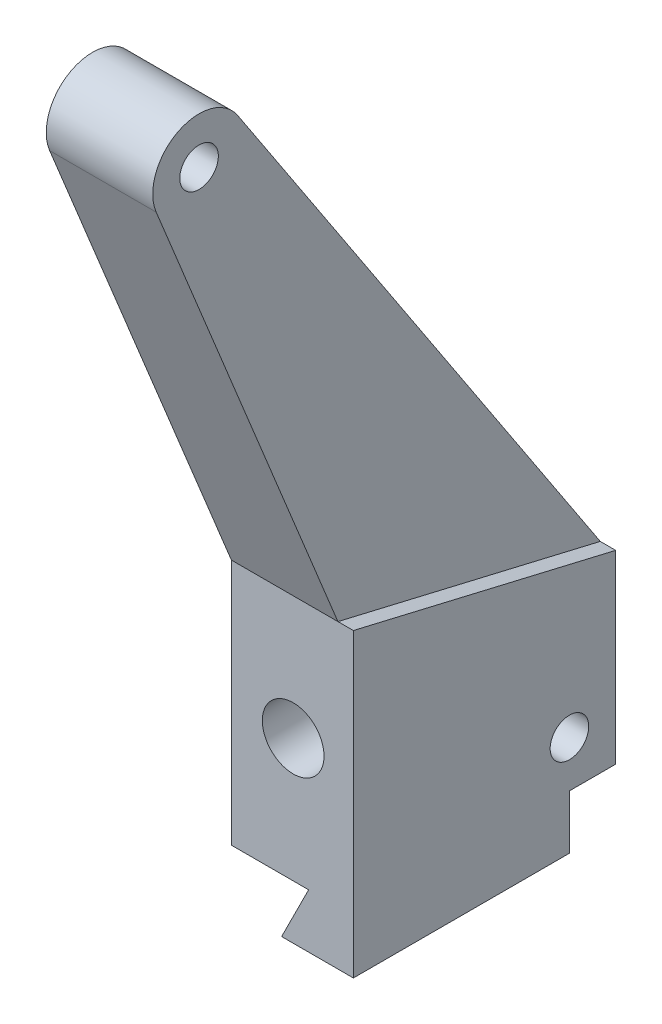
SolidWorks part; units mm, degrees
ref_plane "Front Plane" through (0, 0, 0) normal (0, 0, 1) x (1, 0, 0)
ref_plane "Top Plane" through (0, 0, 0) normal (0, 1, 0) x (1, 0, 0)
ref_plane "Right Plane" through (0, 0, 0) normal (1, 0, 0) x (0, 0, -1)
sketch "Sketch1" plane through (0, 0, 0) normal (1, 0, 0) x (0, 0, -1)
  line L0 (0, 0) -> (0, 16)
  line L1 (0, 16) -> (-23.4951, 51.6508)
  line L2 (-17, 20) -> (-17, 0)
  line L3 (-17, 0) -> (0, 0)
  line L4 (-17, 20) -> (-28.7777, 48.8667)
  arc A0 (-23.4951, 51.6508) -> (-28.7777, 48.8667) centre (-26, 50) ccw
  circle A1 centre (-26, 50) radius 1.25
  dimension "D4" = 6
  dimension "D5" = 9
  dimension "D6" = 50
  dimension "D7" = 2.5
  dimension "D1" = 20
  dimension "D2" = 16
  dimension "D3" = 17
extrude "Boss-Extrude1" add sketch "Sketch1" along normal blind 8
sketch "Sketch2" plane through (8, 0, 0) normal (1, 0, 0) x (0, 0, -1)
  line L0 (-17, 20) -> (-17, 0) construction
  line L1 (-17, 5) -> (0, 5)
  line L2 (-17, 5) -> (-17, 0)
  line L3 (-17, 0) -> (0, 0)
  line L4 (0, 5) -> (0, 0)
  line L5 (0, 0) -> (0, 16) construction
  dimension "D1" = 5
extrude "Cut-Extrude1" [suppressed] cut sketch "Sketch2" against normal blind 4
sketch "Sketch3" plane through (0, 0, 0) normal (0, 0, -1) x (-1, 0, 0)
  line L0 (-8, 0) -> (-5, 0)
  line L1 (-8, 0) -> (0, 0) construction
  line L2 (-5, 0) -> (-3, 4)
  line L3 (-3, 4) -> (-8, 4)
  line L4 (-8, 0) -> (-8, 16) construction
  line L5 (-8, 4) -> (-8, 0)
  dimension "D1" = 5
  dimension "D2" = 3
  dimension "D3" = 4
extrude "Cut-Extrude2" cut sketch "Sketch3" against normal through all
sketch "Sketch5" plane through (8, 0, 0) normal (1, 0, 0) x (0, 0, -1)
  line L0 (0, 4) -> (0, 16) construction
  line L1 (-17, 4) -> (0, 4) construction
  circle A0 centre (-3, 7) radius 1
  dimension "D1" = 2
  dimension "D3" = 3
  dimension "D2" = 3
hole_wizard "M3x0.5 Tapped Hole1" positions "3DSketch1" profile "Sketch6" tap size "M3x0.5" standard "ANSI Metric" end condition through all
sketch3d "3DSketch1"
  point P0 (8, 7, 3)
sketch "Sketch6" plane through (8, 7, 3) normal (0, 1, 0) x (0, 0, -1)
  line L0 (0, 0) -> (0, 16)
  line L1 (0, 16) -> (1.25, 16)
  line L2 (1.25, 16) -> (1.25, 0)
  line L5 (1.25, 0) -> (0, 0)
  line L11 (0, -6.35) -> (0, 107.95) construction
  dimension "Thread Major Dia." = 2.5
  dimension "Thru Tap Drill Depth" = 16
sketch "Sketch7" plane through (0, 0, 0) normal (0, 0, -1) x (-1, 0, 0)
  line L1 (0, 0) -> (-8, 0)
  line L2 (0, 0) -> (0, 0.5)
  line L3 (0, 0.5) -> (-8, 0.5)
  line L4 (-8, 0) -> (-8, 0.5)
  dimension "D1" = 0.5
  dimension "D2" = 8
extrude "Cut-Extrude3" cut sketch "Sketch7" against normal through all
sketch "Sketch8" plane through (0, 0, 17) normal (0, 0, 1) x (1, 0, 0)
  line L0 (3, 4) -> (8, 4) construction
  line L1 (8, 20) -> (8, 4) construction
  circle A0 centre (4, 12) radius 2
  point P4 (5.5, 4)
  dimension "D1" = 4
  dimension "D2" = 8
  dimension "D3" = 4
extrude "Cut-Extrude4" cut sketch "Sketch8" against normal through all
mirror "Mirror1" about plane through (0, 50, 26) normal (1, 0, 0) of "M3x0.5 Tapped Hole1", "Cut-Extrude4", "Cut-Extrude3", "Cut-Extrude2", "Boss-Extrude1"
sketch "Sketch9" plane through (8, 0, 0) normal (1, 0, 0) x (0, 0, -1)
  line L1 (0, 0.5) -> (-38.6719, 0.5)
  line L2 (0, 0.5) -> (0, 56.9511)
  line L3 (0, 56.9511) -> (-38.6719, 56.9511)
  line L4 (-38.6719, 0.5) -> (-38.6719, 56.9511)
extrude "Cut-Extrude5" cut sketch "Sketch9" against normal blind 8.1
sketch "Sketch10" plane through (0, 0, 0) normal (0, 0, -1) x (-1, 0, 0)
  line L0 (4.75, 0.5) -> (3, 4)
  line L1 (3, 4) -> (0.1, 4)
  line L2 (0.1, 0.5) -> (0.1, 16) construction
  line L3 (0.1, 4) -> (0.1, 0.5)
  line L4 (0.1, 0.5) -> (4.75, 0.5)
extrude "Cut-Extrude6" cut sketch "Sketch10" against normal blind 3
sketch "Sketch12" plane through (-0.1, 0, 0) normal (1, 0, 0) x (0, 0, -1)
  line L0 (-17, 20) -> (-28.7777, 48.8667)
  line L1 (0, 16) -> (-23.4951, 51.6508) construction
  line L2 (-23.4951, 51.6508) -> (0, 16)
  line L3 (0, 16) -> (-17, 20)
  arc A0 (-28.7777, 48.8667) -> (-23.4951, 51.6508) centre (-26, 50) cw
  dimension "D1" = 3
extrude "Cut-Extrude8" cut sketch "Sketch12" against normal blind 1
